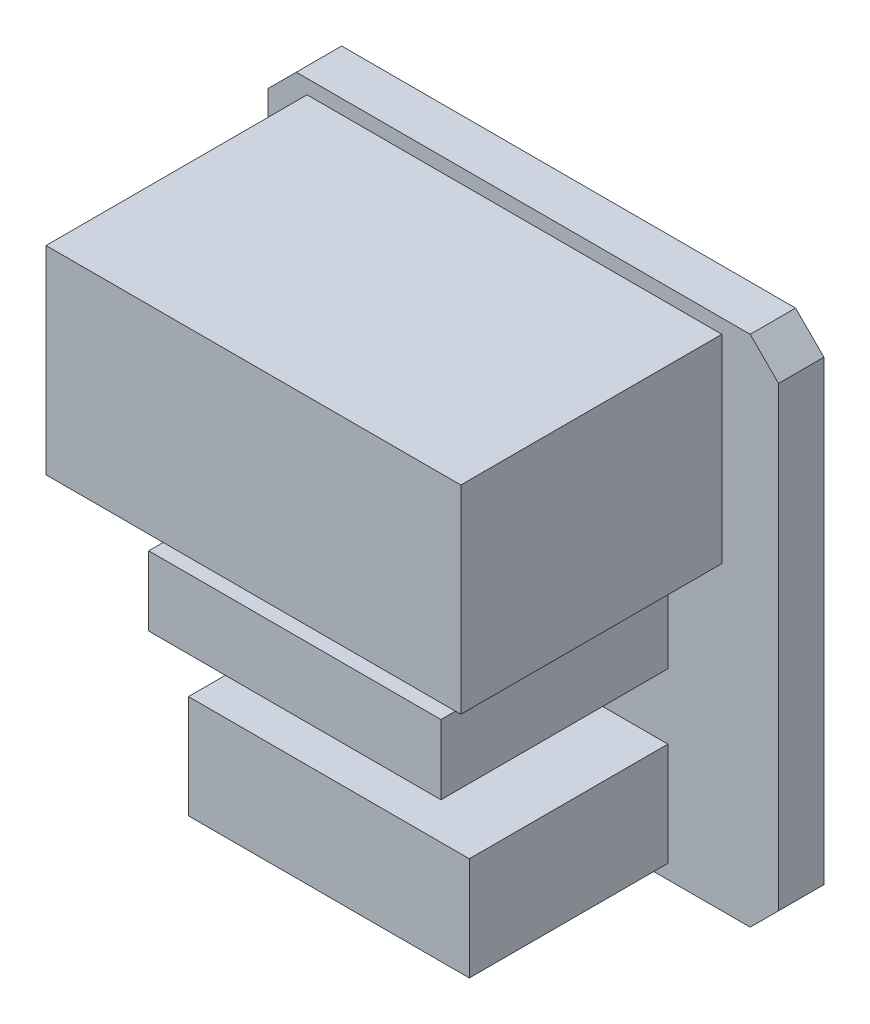
SolidWorks part; units mm, degrees
ref_plane "Front Plane" through (0, 0, 0) normal (0, 0, 1) x (1, 0, 0)
ref_plane "Top Plane" through (0, 0, 0) normal (0, 1, 0) x (1, 0, 0)
ref_plane "Right Plane" through (0, 0, 0) normal (1, 0, 0) x (0, 0, -1)
sketch "Sketch1" plane through (0, 0, 0) normal (0, 0, 1) x (1, 0, 0)
  line L1 (0, 0) -> (18, 0)
  line L2 (0, 0) -> (0, 18.1)
  line L3 (0, 18.1) -> (18, 18.1)
  line L4 (18, 0) -> (18, 18.1)
  dimension "D1" = 18.1
  dimension "D2" = 18
extrude "Boss-Extrude1" add sketch "Sketch1" along normal blind 1.6
chamfer "Chamfer1" distance 1 angle 45 4 edges at (0, 0, 0.8) (18, 0, 0.8) (18, 18.1, 0.8) (0, 18.1, 0.8)
sketch "Sketch2" plane through (0, 0, 1.6) normal (0, 0, 1) x (1, 0, 0)
  line L0 (18, 1) -> (18, 17.1) construction
  line L1 (4.2, 4.14) -> (14.1, 4.14)
  line L2 (4.2, 4.14) -> (4.2, 0.5)
  line L3 (4.2, 0.5) -> (14.1, 0.5)
  line L4 (14.1, 4.14) -> (14.1, 0.5)
  line L5 (1, 0) -> (17, 0) construction
  dimension "D1" = 9.9
  dimension "D2" = 3.64
  dimension "D3" = 3.9
  dimension "D4" = 0.5
extrude "Boss-Extrude2" add sketch "Sketch2" along normal blind 7
sketch "Sketch3" plane through (0, 0, 1.6) normal (0, 0, 1) x (1, 0, 0)
  line L0 (18, 1) -> (18, 17.1) construction
  line L1 (3.8, 8.89) -> (14.1, 8.89)
  line L2 (3.8, 8.89) -> (3.8, 6.44)
  line L3 (3.8, 6.44) -> (14.1, 6.44)
  line L4 (14.1, 8.89) -> (14.1, 6.44)
  line L5 (0, 17.1) -> (0, 1) construction
  line L6 (14.1, 4.14) -> (4.2, 4.14) construction
  dimension "D1" = 2.45
  dimension "D2" = 3.9
  dimension "D3" = 3.8
  dimension "D4" = 2.3
extrude "Boss-Extrude3" add sketch "Sketch3" along normal blind 8
sketch "Sketch4" plane through (0, 0, 1.6) normal (0, 0, 1) x (1, 0, 0)
  line L0 (0, 17.1) -> (0, 1) construction
  line L1 (1.38, 17.6) -> (16, 17.6)
  line L2 (1.38, 17.6) -> (1.38, 10.6)
  line L3 (1.38, 10.6) -> (16, 10.6)
  line L4 (16, 17.6) -> (16, 10.6)
  line L5 (18, 1) -> (18, 17.1) construction
  line L6 (17, 18.1) -> (1, 18.1) construction
  dimension "D1" = 7
  dimension "D2" = 1.38
  dimension "D3" = 2
  dimension "D4" = 0.5
extrude "Boss-Extrude4" add sketch "Sketch4" along normal blind 9.2
